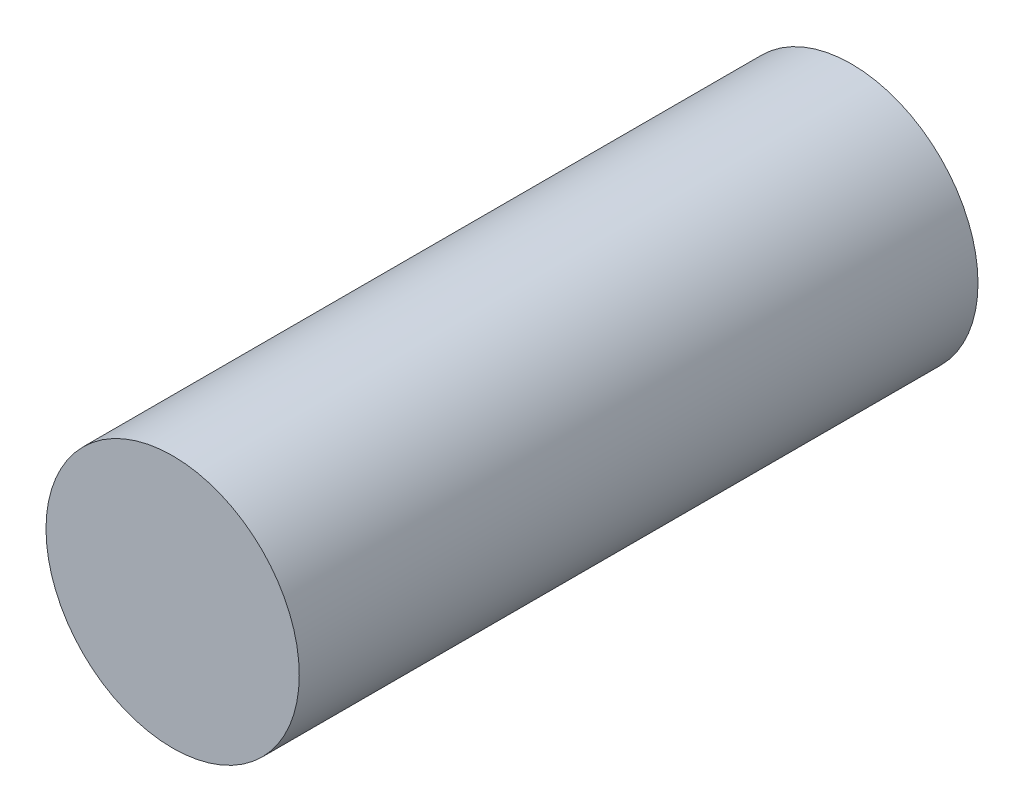
SolidWorks part; units mm, degrees
material "6061-T6 (SS)"
ref_plane "Front Plane" through (0, 0, 0) normal (0, 0, 1) x (1, 0, 0)
ref_plane "Top Plane" through (0, 0, 0) normal (0, 1, 0) x (1, 0, 0)
ref_plane "Right Plane" through (0, 0, 0) normal (1, 0, 0) x (0, 0, -1)
sketch "Body sketch" plane through (0, 0, 0) normal (0, 0, 1) x (1, 0, 0)
  circle A0 centre (0, 0) radius 2.5
extrude "Body" add sketch "Body sketch" along normal blind 13.4
